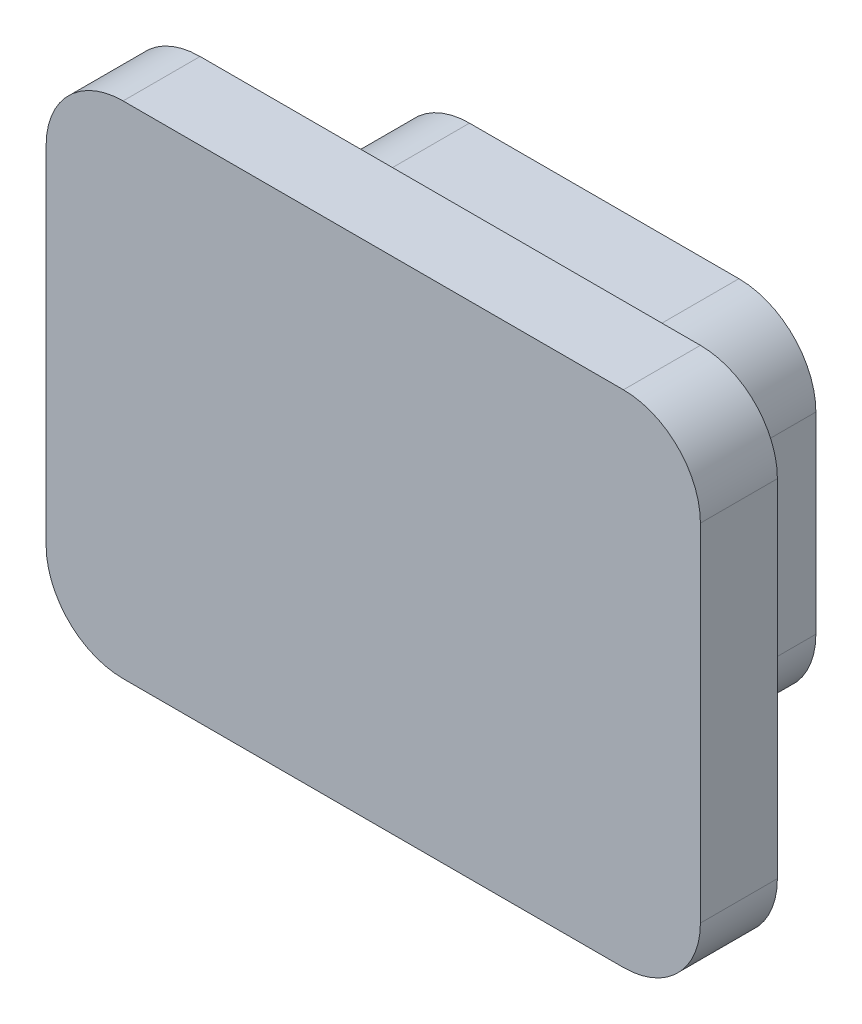
SolidWorks part; units mm, degrees
ref_plane "Спереди" through (0, 0, 0) normal (0, 0, 1) x (1, 0, 0)
ref_plane "Сверху" through (0, 0, 0) normal (0, 1, 0) x (1, 0, 0)
ref_plane "Справа" through (0, 0, 0) normal (1, 0, 0) x (0, 0, -1)
sketch "Эскиз1" plane through (0, 0, 0) normal (0, 0, 1) x (1, 0, 0)
  line L1 (-1.75, -2.25) -> (1.75, -2.25)
  line L2 (-2.75, -1.25) -> (-2.75, 1.25)
  line L3 (-1.75, 2.25) -> (1.75, 2.25)
  line L4 (2.75, -1.25) -> (2.75, 1.25)
  line L5 (-2.75, -2.25) -> (2.75, 2.25) construction
  line L6 (-2.75, 2.25) -> (2.75, -2.25) construction
  arc A1 (1.75, -2.25) -> (2.75, -1.25) centre (1.75, -1.25) ccw
  arc A2 (2.75, 1.25) -> (1.75, 2.25) centre (1.75, 1.25) ccw
  arc A3 (-1.75, -2.25) -> (-2.75, -1.25) centre (-1.75, -1.25) cw
  arc A4 (-2.75, 1.25) -> (-1.75, 2.25) centre (-1.75, 1.25) cw
  point P0 (0, 0)
  dimension "D1" = 5.5
  dimension "D3" = 1
  dimension "D2" = 4.5
extrude "Бобышка-Вытянуть1" add sketch "Эскиз1" along normal blind 2
sketch "Эскиз2" plane through (0, 0, 2) normal (0, 0, 1) x (1, 0, 0)
  line L1 (-3.25, -3.25) -> (3.25, -3.25)
  line L2 (-4.25, -2.25) -> (-4.25, 2.25)
  line L3 (-3.25, 3.25) -> (3.25, 3.25)
  line L4 (4.25, -2.25) -> (4.25, 2.25)
  line L5 (-4.25, -3.25) -> (4.25, 3.25) construction
  line L6 (-4.25, 3.25) -> (4.25, -3.25) construction
  arc A0 (-4.25, -2.25) -> (-3.25, -3.25) centre (-3.25, -2.25) ccw
  arc A1 (3.25, -3.25) -> (4.25, -2.25) centre (3.25, -2.25) ccw
  arc A2 (4.25, 2.25) -> (3.25, 3.25) centre (3.25, 2.25) ccw
  arc A3 (-4.25, 2.25) -> (-3.25, 3.25) centre (-3.25, 2.25) cw
  point P0 (0, 0)
  dimension "D3" = 1
  dimension "D1" = 8.5
  dimension "D2" = 6.5
extrude "Бобышка-Вытянуть2" add sketch "Эскиз2" along normal blind 1
